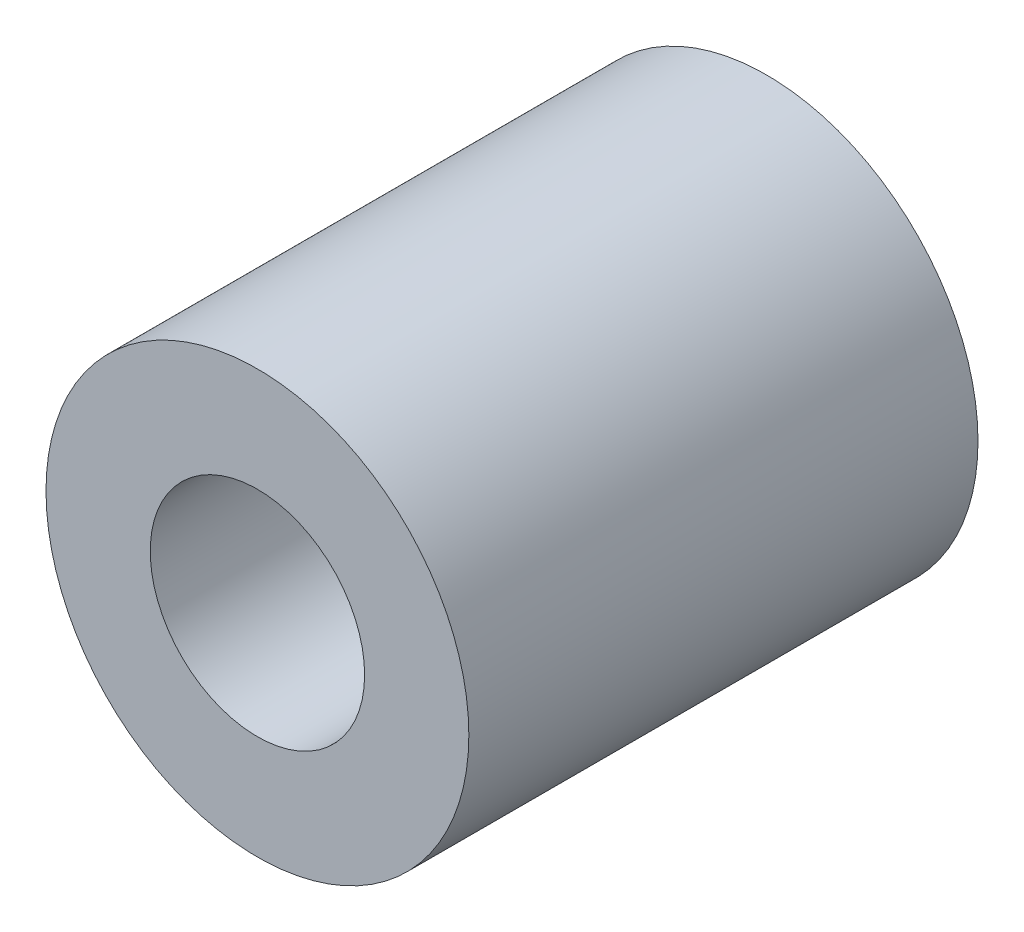
SolidWorks part; units mm, degrees
ref_plane "Plan de face" through (0, 0, 0) normal (1, 0, 0) x (0, 1, 0)
ref_plane "Plan de dessus" through (0, 0, 0) normal (0, 0, 1) x (0, 1, 0)
ref_plane "Plan de droite" through (0, 0, 0) normal (0, 1, 0) x (-1, 0, 0)
sketch "Esquisse1" plane through (0, 0, 0) normal (0, 0, 1) x (0, 1, 0)
  circle A0 centre (0, 0) radius 4
  circle A1 centre (0, 0) radius 7.89
  dimension "D1" = 15.78
  dimension "D2" = 8
extrude "Boss.-Extru.1" add sketch "Esquisse1" along normal blind 19
